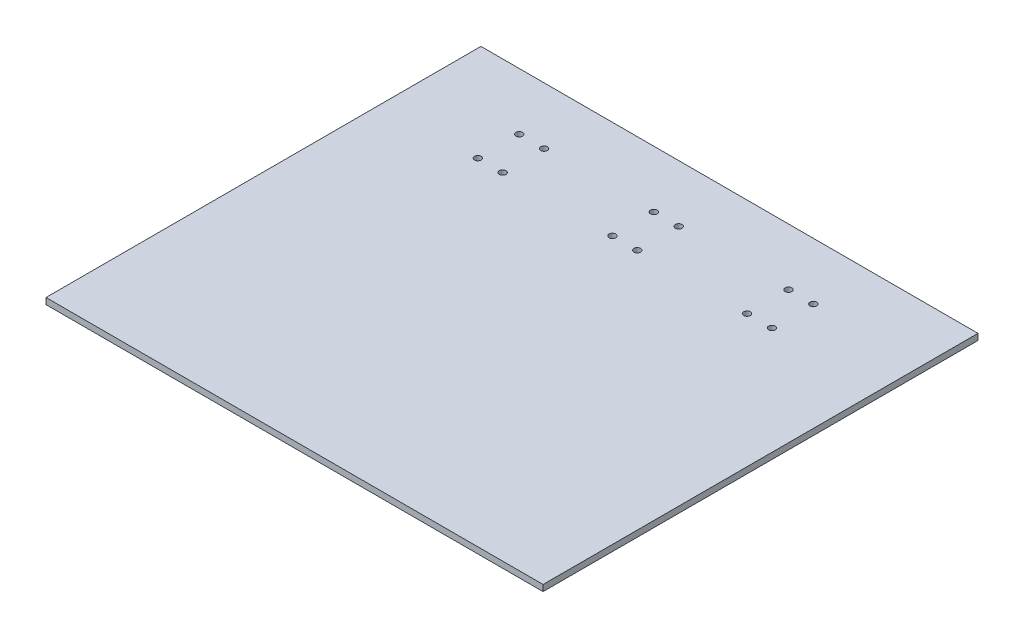
SolidWorks part; units mm, degrees
ref_plane "前视基准面" through (0, 0, 0) normal (0, 0, 1) x (1, 0, 0)
ref_plane "上视基准面" through (0, 0, 0) normal (0, 1, 0) x (1, 0, 0)
ref_plane "右视基准面" through (0, 0, 0) normal (1, 0, 0) x (0, 0, -1)
sketch "草图1" plane through (0, 0, 0) normal (0, 1, 0) x (1, 0, 0)
  line L1 (-120, 105) -> (120, 105)
  line L2 (-120, 105) -> (-120, -105)
  line L3 (-120, -105) -> (120, -105)
  line L4 (120, 105) -> (120, -105)
  line L5 (-120, 105) -> (120, -105) construction
  line L6 (-120, -105) -> (120, 105) construction
  point P0 (0, 0)
  dimension "D1" = 240
  dimension "D2" = 210
extrude "凸台-拉伸1" add sketch "草图1" along normal blind 3
sketch "草图2" plane through (0, 3, 0) normal (0, 1, 0) x (1, 0, 0)
  line L0 (-120, 77.5) -> (120, 77.5) construction
  line L1 (-120, 105) -> (-120, -105) construction
  line L2 (120, -105) -> (120, 105) construction
  line L3 (120, 57.5) -> (-120, 57.5) construction
  line L4 (68, 77.5) -> (68, 57.5) construction
  line L5 (56, 77.5) -> (56, 57.5) construction
  line L6 (120, 105) -> (-120, 105) construction
  circle A0 centre (68, 77.5) radius 1.6
  circle A1 centre (56, 77.5) radius 1.6
  circle A2 centre (56, 57.5) radius 1.6
  circle A3 centre (68, 57.5) radius 1.6
  dimension "D1" = 3.2
  dimension "D3" = 20
  dimension "D2" = 12
  dimension "D4" = 27.5
  dimension "D5" = 52
extrude "切除-拉伸1" cut sketch "草图2" against normal through all both and the other way through all
pattern_linear "阵列(线性)1" count 3 spacing 65 along (-1, 0, 0) of "切除-拉伸1"
